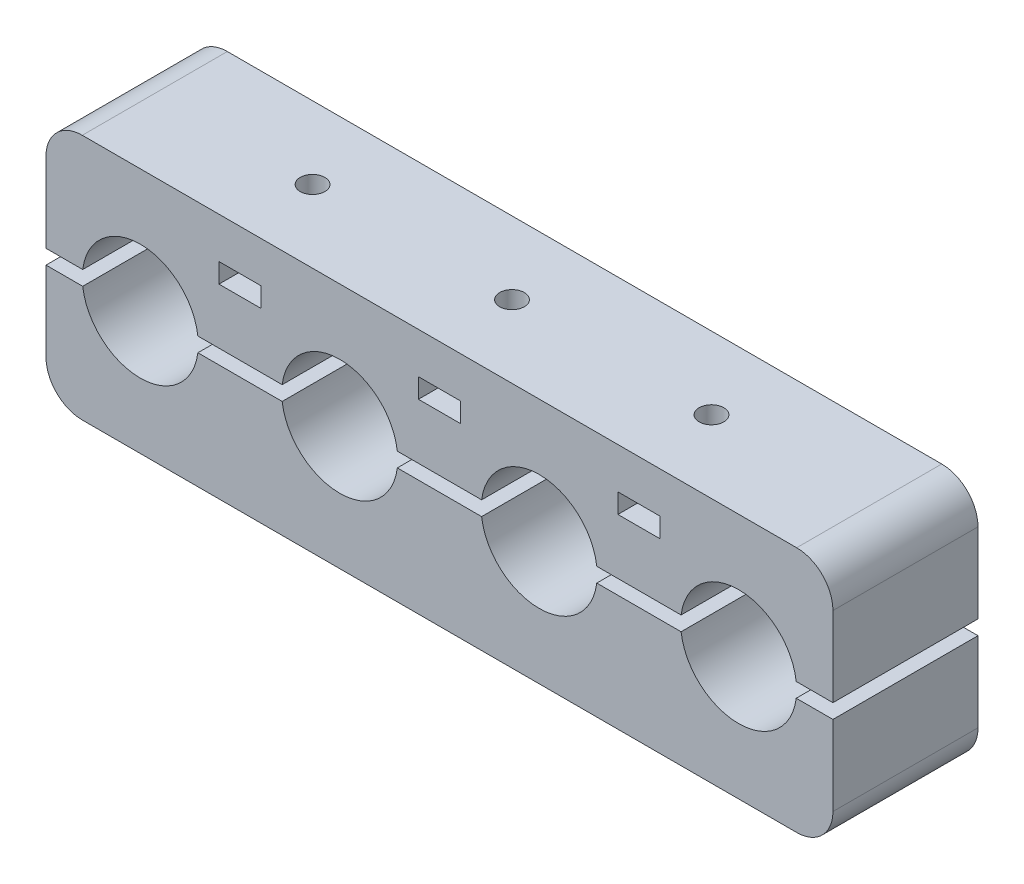
SolidWorks part; units mm, degrees
ref_plane "Piano frontale" through (0, 0, 0) normal (0, 0, 1) x (1, 0, 0)
ref_plane "Piano superiore" through (0, 0, 0) normal (0, 1, 0) x (1, 0, 0)
ref_plane "Piano destro" through (0, 0, 0) normal (1, 0, 0) x (0, 0, -1)
sketch "Schizzo1" plane through (0, 0, 0) normal (0, 0, 1) x (1, 0, 0)
  line L0 (0, 0) -> (-13, 0) construction
  line L1 (-13, 0) -> (-13, 17) construction
  line L2 (-13, 0) -> (-13, 1) construction
  line L3 (-8, 17) -> (90.5, 17)
  line L4 (-13, 12) -> (-13, -12)
  line L5 (-8, -17) -> (90.5, -17)
  line L6 (95.5, 12) -> (95.5, -12)
  line L8 (-13, 1) -> (95.5, 1)
  line L9 (-13, 1) -> (-13, -1)
  line L10 (-13, -1) -> (95.5, -1)
  line L11 (95.5, 1) -> (95.5, -1)
  circle A0 centre (0, 0) radius 8
  circle A1 centre (27.5, 0) radius 8
  circle A2 centre (55, 0) radius 8
  circle A3 centre (82.5, 0) radius 8
  circle A6 centre (0, 0) radius 11.5 construction
  arc A7 (90.5, 17) -> (95.5, 12) centre (90.5, 12) cw
  arc A8 (90.5, -17) -> (95.5, -12) centre (90.5, -12) ccw
  arc A9 (-13, -12) -> (-8, -17) centre (-8, -12) ccw
  arc A10 (-13, 12) -> (-8, 17) centre (-8, 12) cw
  dimension "D1" = 4
  dimension "D2" = 5
extrude "Estrusione-Estrusione1" add sketch "Schizzo1" along normal blind 20 contours A10 L4 L8 A0 A1 A2 A3 L6 A7 L3 | L4 A9 L5 A8 L6 L10 A3 A2 A1 A0
sketch "Schizzo2" plane through (0, 0, 20) normal (0, 0, 1) x (1, 0, 0)
  line L0 (13.75, 1) -> (13.75, 17) construction
  line L1 (7.9373, 1) -> (19.5627, 1) construction
  line L2 (-8, 17) -> (90.5, 17) construction
  line L3 (41.25, 1) -> (41.25, 17) construction
  line L5 (35.4373, 1) -> (47.0627, 1) construction
  line L6 (68.75, 1) -> (68.75, 17) construction
  line L7 (62.9373, 1) -> (74.5627, 1) construction
  line L8 (13.75, 17) -> (13.75, 10) construction
  line L9 (10.85, 8.65) -> (16.65, 8.65)
  line L10 (10.85, 8.65) -> (10.85, 11.35)
  line L11 (16.65, 8.65) -> (16.65, 11.35)
  line L12 (10.85, 11.35) -> (16.65, 11.35)
  line L13 (10.85, 8.65) -> (16.65, 11.35) construction
  line L14 (16.65, 8.65) -> (10.85, 11.35) construction
  line L15 (38.35, 11.35) -> (44.15, 11.35)
  line L16 (38.35, 8.65) -> (44.15, 8.65)
  line L17 (38.35, 8.65) -> (38.35, 11.35)
  line L18 (44.15, 8.65) -> (44.15, 11.35)
  line L19 (65.85, 11.35) -> (71.65, 11.35)
  line L20 (65.85, 8.65) -> (71.65, 8.65)
  line L21 (65.85, 8.65) -> (65.85, 11.35)
  line L22 (71.65, 8.65) -> (71.65, 11.35)
  dimension "D1" = 3
extrude "Taglio-Estrusione1" cut sketch "Schizzo2" against normal blind 20
sketch "Schizzo3" plane through (0, -17, 0) normal (0, -1, 0) x (1, 0, 0)
  line L0 (41.25, 20) -> (41.25, 0) construction
  line L1 (-8, 20) -> (90.5, 20) construction
  line L2 (-8, 0) -> (90.5, 0) construction
  line L3 (41.25, 10) -> (68.75, 10) construction
  line L4 (41.25, 10) -> (13.75, 10) construction
hole_wizard "Foro per Vite M3-1" positions "Schizzo4" profile "Schizzo5" hole size "M3" standard "Ansi Metric"
sketch "Schizzo4" plane through (0, -17, 0) normal (0, -1, 0) x (-1, 0, 0)
  point P0 (-68.75, -10)
  point P3 (-41.25, -10)
  point P6 (-13.75, -10)
sketch "Schizzo5" plane through (68.75, -17, 10) normal (1, 0, 0) x (0, 0, -1)
  line L0 (0, 0) -> (0, 40)
  line L1 (0, 40) -> (1.7, 38.9785)
  line L2 (1.7, 38.9785) -> (1.7, 0)
  line L5 (1.7, 0) -> (0, 0)
  line L10 (0, 40) -> (-1.7, 38.9785) construction
  line L11 (0, -6.35) -> (0, 107.95) construction
  dimension "Hole Dia." = 3.4
  dimension "Hole Depth" = 40
  dimension "Drill Angle" = 118
